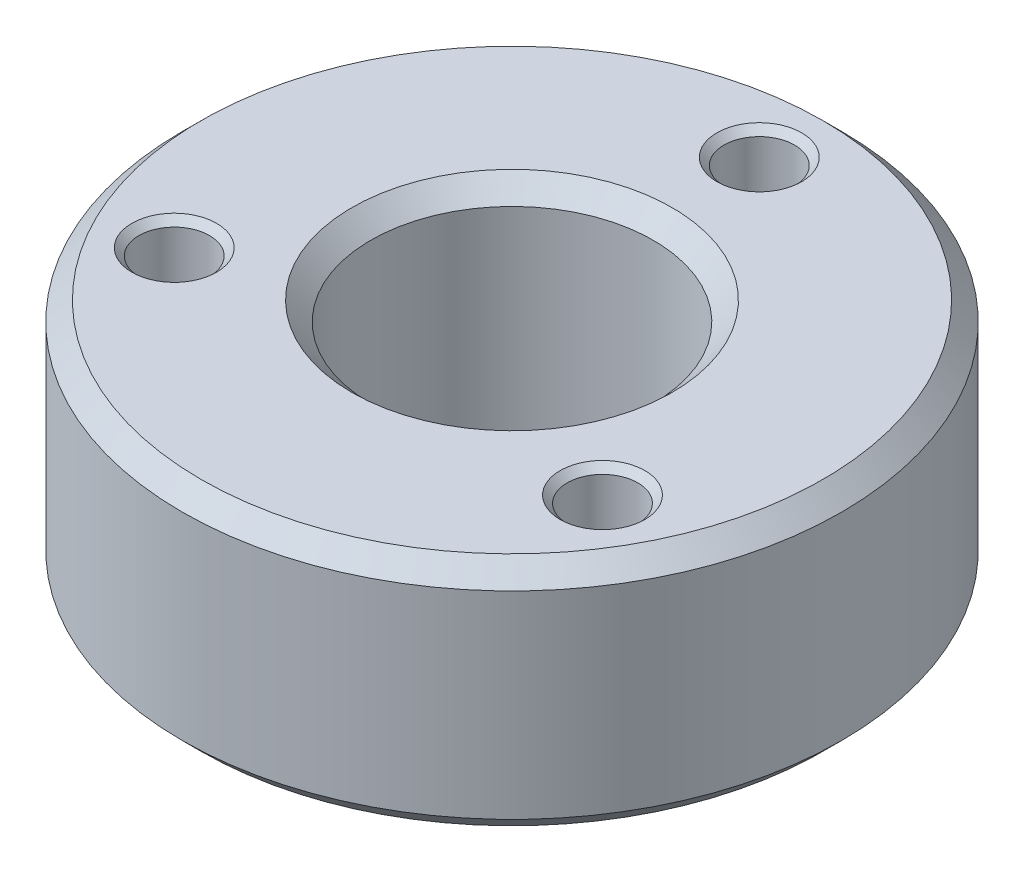
SolidWorks part; units mm, degrees
ref_plane "Front Plane" through (0, 0, 0) normal (0, 0, 1) x (1, 0, 0)
ref_plane "Top Plane" through (0, 0, 0) normal (0, 1, 0) x (1, 0, 0)
ref_plane "Right Plane" through (0, 0, 0) normal (1, 0, 0) x (0, 0, -1)
sketch "Sketch1" plane through (0, 0, 0) normal (0, 1, 0) x (1, 0, 0)
  circle A0 centre (0, 0) radius 14
extrude "Boss-Extrude1" add sketch "Sketch1" along normal blind 10
sketch "Sketch2" plane through (0, 10, 0) normal (0, 1, 0) x (1, 0, 0)
  circle A0 centre (0, 0) radius 6
extrude "Cut-Extrude1" cut sketch "Sketch2" against normal through all
sketch "Sketch3" plane through (0, 10, 0) normal (0, 1, 0) x (1, 0, 0)
  line L0 (0, 10.5) -> (0, 0) construction
  circle A1 centre (0, 10.5) radius 1.5
  dimension "D2" = 3
  dimension "D1" = 10.5
extrude "Cut-Extrude2" cut sketch "Sketch3" against normal through all
chamfer "Chamfer1" distance 0.8 4 edges at (0, 0, 14) (0, 0, 6) (0, 10, 14) (0, 10, 6)
chamfer "Chamfer2" distance 0.3 2 edges at (0, 0, -9) (0, 10, -9)
pattern_circular "CirPattern1" count 3 over 360 about axis through (0, 0, 0) along (0, 1, 0) of "Cut-Extrude2", "Chamfer2"
